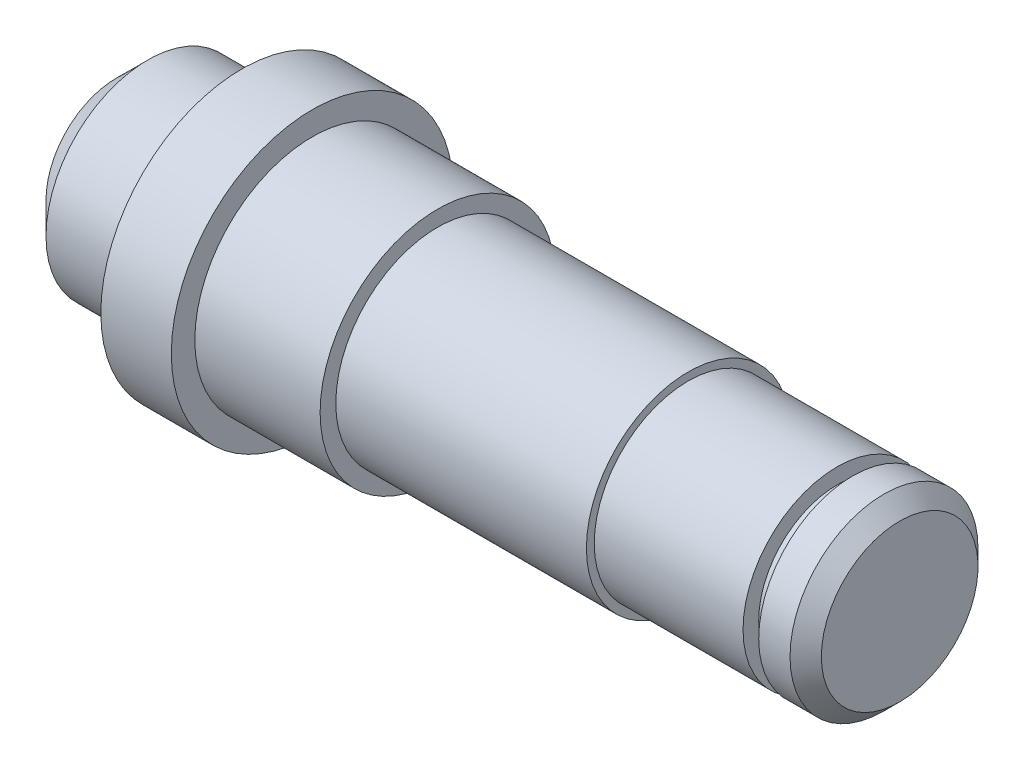
SolidWorks part; units mm, degrees
ref_plane "Plan1" through (0, 0, 0) normal (0, 0, 1) x (1, 0, 0)
ref_plane "Plan2" through (0, 0, 0) normal (0, 1, 0) x (1, 0, 0)
ref_plane "Plan3" through (0, 0, 0) normal (1, 0, 0) x (0, 0, -1)
sketch "Esquisse1" plane through (0, 0, 0) normal (0, 0, 1) x (1, 0, 0)
  line L0 (0, 0) -> (55, 0) construction
  line L1 (0, 0) -> (0, 4.5)
  line L2 (0, 4.5) -> (2, 6.5)
  line L3 (2, 6.5) -> (8, 6.5)
  line L4 (8, 6.5) -> (8, 9)
  line L5 (8, 9) -> (12.5, 9)
  line L6 (12.5, 9) -> (12.5, 7.5)
  line L7 (12.5, 7.5) -> (20.5, 7.5)
  line L8 (20.5, 7.5) -> (20.5, 6.5)
  line L9 (20.5, 6.5) -> (36.5, 6.5)
  line L10 (36.5, 6.5) -> (36.5, 6)
  line L11 (36.5, 6) -> (46, 6)
  line L12 (46, 6) -> (46, 5)
  line L13 (46, 5) -> (47, 5)
  line L14 (47, 5) -> (47, 6)
  line L15 (47, 6) -> (49, 6)
  line L16 (49, 6) -> (50, 5)
  line L17 (50, 5) -> (50, 0)
  line L18 (0, 0) -> (50, 0)
  dimension "D1" = 45
  dimension "D2" = 2
  dimension "D3" = 13
  dimension "D4" = 8
  dimension "D5" = 18
  dimension "D6" = 4.5
  dimension "D7" = 8
  dimension "D8" = 13
  dimension "D9" = 16
  dimension "D10" = 15
  dimension "D11" = 9.5
  dimension "D12" = 12
  dimension "D13" = 1
  dimension "D14" = 10
  dimension "D15" = 45
  dimension "D16" = 1
  dimension "D17" = 3
revolve "Base-Révolution" add sketch "Esquisse1" angle 360 about L0
